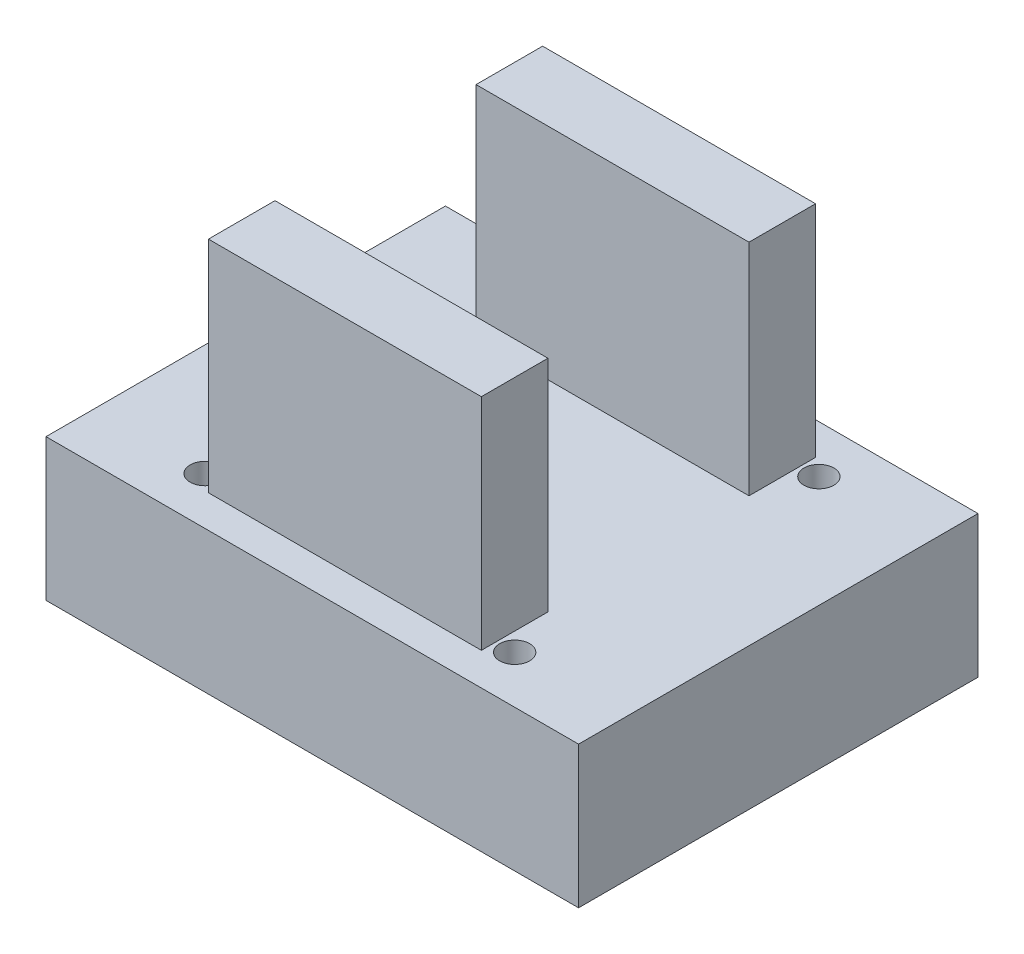
SolidWorks part; units mm, degrees
ref_plane "Front Plane" through (0, 0, 0) normal (0, 0, 1) x (1, 0, 0)
ref_plane "Top Plane" through (0, 0, 0) normal (0, 1, 0) x (1, 0, 0)
ref_plane "Right Plane" through (0, 0, 0) normal (1, 0, 0) x (0, 0, -1)
sketch "Sketch1" plane through (0, 0, 0) normal (0, 1, 0) x (1, 0, 0)
  line L1 (0, 0) -> (20.32, 0)
  line L2 (0, 0) -> (0, 15.24)
  line L3 (0, 15.24) -> (20.32, 15.24)
  line L4 (20.32, 0) -> (20.32, 15.24)
  dimension "D1" = 20.32
  dimension "D2" = 15.24
extrude "Boss-Extrude1" add sketch "Sketch1" along normal blind 5.4102
sketch "Sketch2" plane through (0, 5.4102, 0) normal (0, 1, 0) x (1, 0, 0)
  line L0 (0, 7.62) -> (20.32, 7.62) construction
  line L1 (0, 15.24) -> (0, 0) construction
  line L2 (20.32, 0) -> (20.32, 15.24) construction
  line L4 (4.953, 13.9954) -> (15.367, 13.9954)
  line L5 (4.953, 13.9954) -> (4.953, 11.4554)
  line L6 (4.953, 11.4554) -> (15.367, 11.4554)
  line L7 (15.367, 13.9954) -> (15.367, 11.4554)
  line L8 (10.16, 7.62) -> (10.16, 15.2908) construction
  line L9 (4.953, 3.7846) -> (15.367, 3.7846)
  line L10 (15.367, 1.2446) -> (15.367, 3.7846)
  line L11 (4.953, 1.2446) -> (15.367, 1.2446)
  line L12 (4.953, 1.2446) -> (4.953, 3.7846)
  point P14 (10.16, 11.4554)
  dimension "D1" = 2.54
  dimension "D2" = 10.414
  dimension "D3" = 12.7508
extrude "Boss-Extrude2" add sketch "Sketch2" along normal blind 8.382
sketch "Sketch3" plane through (0, 0, 0) normal (0, -1, 0) x (1, 0, 0)
  line L0 (0, -7.62) -> (20.32, -7.62) construction
  line L1 (0, -15.24) -> (0, 0) construction
  line L2 (4.2545, -1.8161) -> (16.0655, -1.8161) construction
  line L3 (20.32, 0) -> (20.32, -15.24) construction
  line L4 (10.16, -7.62) -> (10.16, 3.9878) construction
  line L5 (4.2545, -13.4239) -> (16.0655, -13.4239) construction
  circle A0 centre (4.2545, -1.8161) radius 0.5715
  circle A1 centre (16.0655, -1.8161) radius 0.5715
  circle A2 centre (16.0655, -13.4239) radius 0.5715
  circle A3 centre (4.2545, -13.4239) radius 0.5715
  point P8 (10.16, -1.8161)
  dimension "D2" = 1.143
  dimension "D3" = 11.6078
  dimension "D1" = 11.811
extrude "Cut-Extrude1" cut sketch "Sketch3" against normal up to surface (5.4102 mm away) contours A1 | A0 | A2 | A3 up to face at (10.16, 5.4102, -12.7254)
